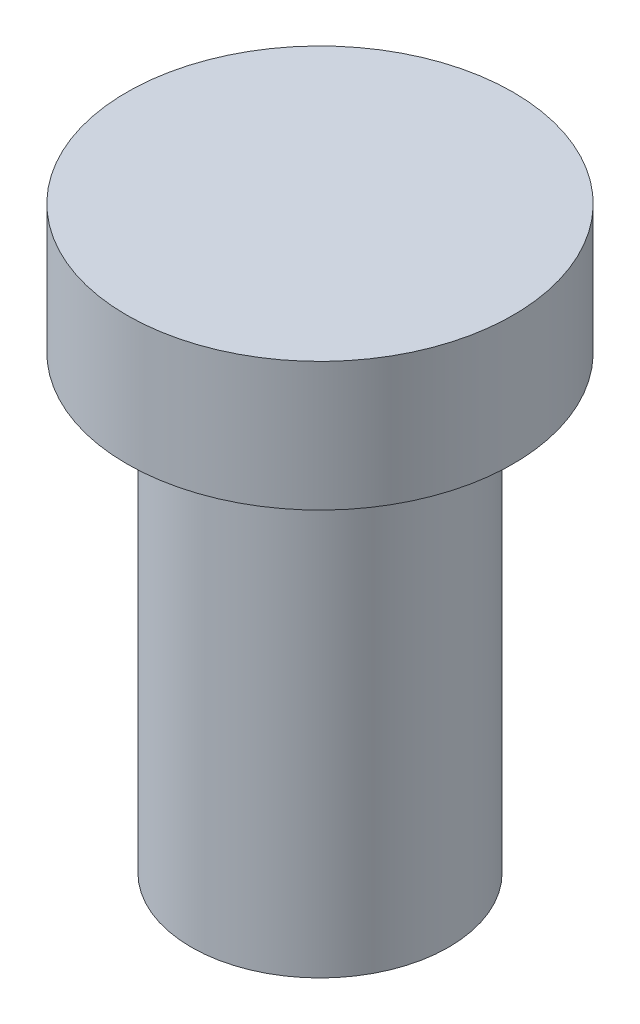
SolidWorks part; units mm, degrees
ref_plane "정면" through (0, 0, 0) normal (0, 0, 1) x (1, 0, 0)
ref_plane "윗면" through (0, 0, 0) normal (0, 1, 0) x (1, 0, 0)
ref_plane "우측면" through (0, 0, 0) normal (1, 0, 0) x (0, 0, -1)
sketch "스케치1" plane through (0, 0, 0) normal (1, 0, 0) x (0, 0, -1)
  line L0 (0, 20.9905) -> (0, -20.0677) construction
  line L1 (0, 16.2462) -> (3, 16.2462)
  line L2 (3, 16.2462) -> (3, 14.2462)
  line L3 (3, 14.2462) -> (2, 14.2462)
  line L4 (2, 14.2462) -> (2, 7.2462)
  line L5 (2, 7.2462) -> (0, 7.2462)
  line L6 (0, 16.2462) -> (0, 7.2462)
  dimension "D1" = 7
  dimension "D2" = 2
  dimension "D3" = 3
  dimension "D4" = 2
revolve "회전1" add sketch "스케치1" angle 360 about L0
